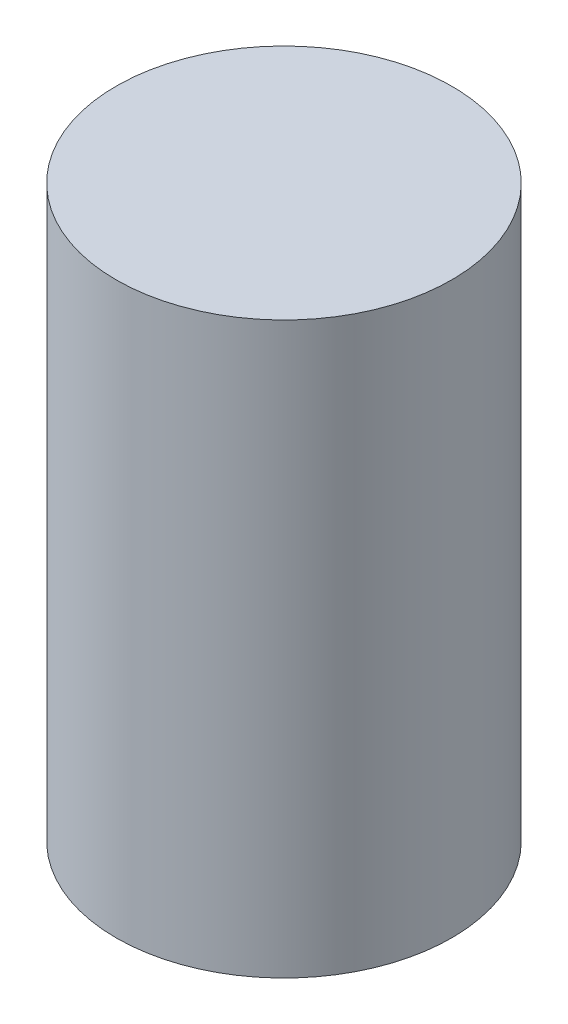
SolidWorks part; units mm, degrees
ref_plane "Plan de face" through (0, 0, 0) normal (0, 0, 1) x (1, 0, 0)
ref_plane "Plan de dessus" through (0, 0, 0) normal (0, 1, 0) x (1, 0, 0)
ref_plane "Plan de droite" through (0, 0, 0) normal (1, 0, 0) x (0, 0, -1)
sketch "Esquisse1" plane through (0, 0, 0) normal (0, 1, 0) x (1, 0, 0)
  circle A0 centre (0, 0) radius 73.61
  dimension "D1" = 147.22
extrude "Boss.-Extru.1" add sketch "Esquisse1" along normal blind 250
